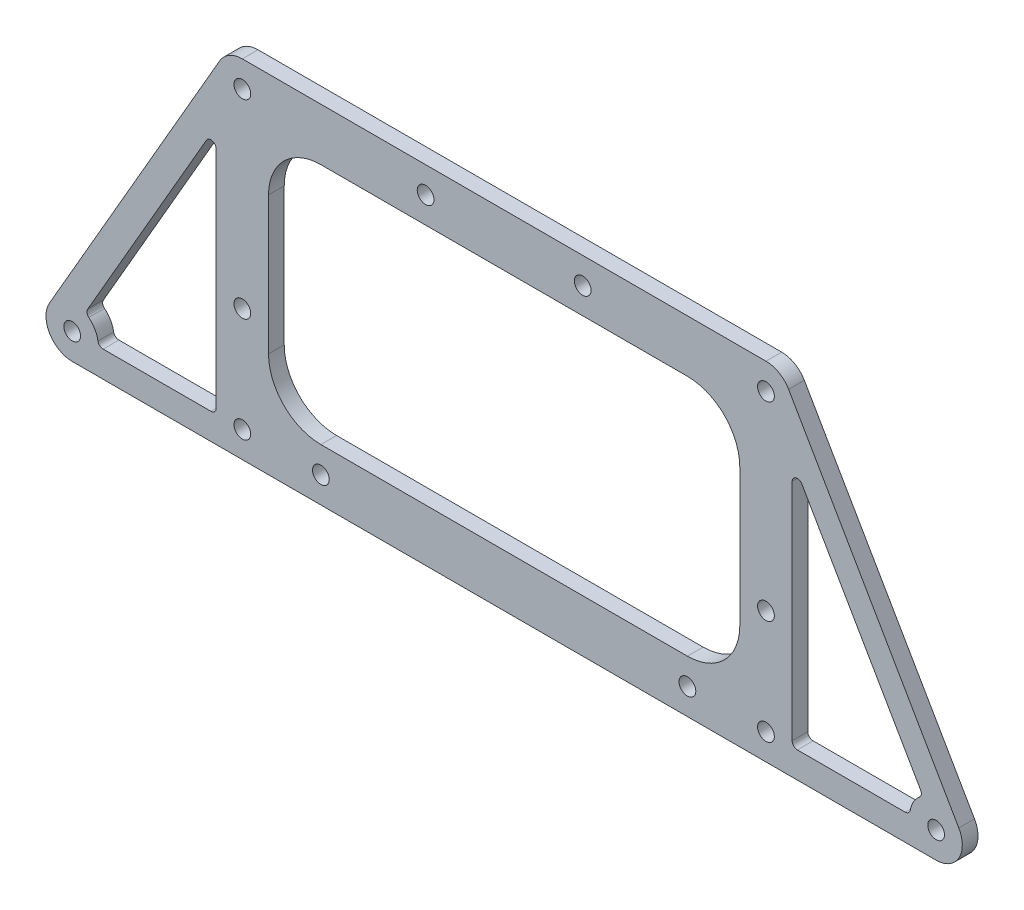
SolidWorks part; units mm, degrees
material "6061 合金"
ref_plane "正面" through (0, 0, 0) normal (0, 0, 1) x (1, 0, 0)
ref_plane "平面" through (0, 0, 0) normal (0, 1, 0) x (1, 0, 0)
ref_plane "右側面" through (0, 0, 0) normal (1, 0, 0) x (0, 0, -1)
sketch "ｽｹｯﾁ1" plane through (0, 0, 0) normal (0, 0, 1) x (1, 0, 0)
  line L0 (-50, 28.1458) -> (-82.5, -28.1458) construction
  line L1 (50, -28.1458) -> (-50, -28.1458) construction
  line L2 (50, -28.1458) -> (50, 28.1458) construction
  line L3 (50, 28.1458) -> (-50, 28.1458) construction
  line L4 (-50, -28.1458) -> (-50, 28.1458) construction
  line L5 (50, -28.1458) -> (-50, 28.1458) construction
  line L6 (50, 28.1458) -> (-50, -28.1458) construction
  line L7 (-82.5, -28.1458) -> (-50, -28.1458) construction
  line L8 (50, 28.1458) -> (82.5, -28.1458) construction
  line L9 (82.5, -28.1458) -> (50, -28.1458) construction
  line L10 (50, 33.1458) -> (-50, 33.1458)
  line L11 (-54.3301, 30.6458) -> (-86.8301, -25.6458)
  line L12 (-82.5, -33.1458) -> (-50, -33.1458)
  line L13 (50, -33.1458) -> (-50, -33.1458)
  line L14 (82.5, -33.1458) -> (50, -33.1458)
  line L15 (54.3301, 30.6458) -> (86.8301, -25.6458)
  line L21 (45, 23.1458) -> (-45, 23.1458)
  line L22 (-45, -23.1458) -> (-45, 23.1458)
  line L23 (45, -23.1458) -> (-45, -23.1458)
  line L24 (45, -23.1458) -> (45, 23.1458)
  line L25 (-55, 19.4856) -> (-55, -28.1458)
  line L26 (-55, -28.1458) -> (-77.5, -28.1458)
  line L27 (-80, -23.8157) -> (-55, 19.4856)
  line L28 (0, 23.1458) -> (0, -23.1458) construction
  line L29 (55, -28.1458) -> (77.5, -28.1458)
  line L30 (55, 19.4856) -> (55, -28.1458)
  line L31 (80, -23.8157) -> (55, 19.4856)
  arc A0 (-86.8301, -25.6458) -> (-82.5, -33.1458) centre (-82.5, -28.1458) ccw
  arc A1 (82.5, -33.1458) -> (86.8301, -25.6458) centre (82.5, -28.1458) ccw
  arc A2 (50, 33.1458) -> (54.3301, 30.6458) centre (50, 28.1458) cw
  arc A3 (-50, 33.1458) -> (-54.3301, 30.6458) centre (-50, 28.1458) ccw
  circle A4 centre (-50, 28.1458) radius 1.6
  circle A5 centre (-82.5, -28.1458) radius 1.6
  circle A6 centre (50, 28.1458) radius 1.6
  circle A7 centre (82.5, -28.1458) radius 1.6
  circle A8 centre (-50, -28.1458) radius 1.6
  circle A9 centre (50, -28.1458) radius 1.6
  arc A11 (-80, -23.8157) -> (-77.5, -28.1458) centre (-82.5, -28.1458) cw
  arc A12 (80, -23.8157) -> (77.5, -28.1458) centre (82.5, -28.1458) ccw
  circle A13 centre (-35, -28.1458) radius 1.6
  circle A14 centre (35, -28.1458) radius 1.6
  circle A15 centre (-15, 28.1458) radius 1.6
  circle A16 centre (15, 28.1458) radius 1.6
  circle A17 centre (-50, -8.1458) radius 1.6
  circle A22 centre (50, -8.1458) radius 1.6
  point P0 (0, 0)
  dimension "D5" = 5
  dimension "D6" = 3.2
  dimension "D2" = 65
  dimension "D4" = 70
  dimension "D9" = 30
  dimension "D10" = 20
  dimension "D1" = 100
  dimension "D3" = 30
  dimension "D8" = 10
  dimension "D7" = 5
extrude "ﾎﾞｽ - 押し出し1" add sketch "ｽｹｯﾁ1" along normal blind 3
fillet "ﾌｨﾚｯﾄ1" radius 1 8 edges at (77.5, -28.1458, 1.5) (80, -23.8157, 1.5) (55, -28.1458, 1.5) (55, 19.4856, 1.5) (-55, 19.4856, 1.5) (-55, -28.1458, 1.5) (-80, -23.8157, 1.5) (-77.5, -28.1458, 1.5)
fillet "ﾌｨﾚｯﾄ2" radius 10 4 edges at (45, 23.1458, 1.5) (45, -23.1458, 1.5) (-45, -23.1458, 1.5) (-45, 23.1458, 1.5)
